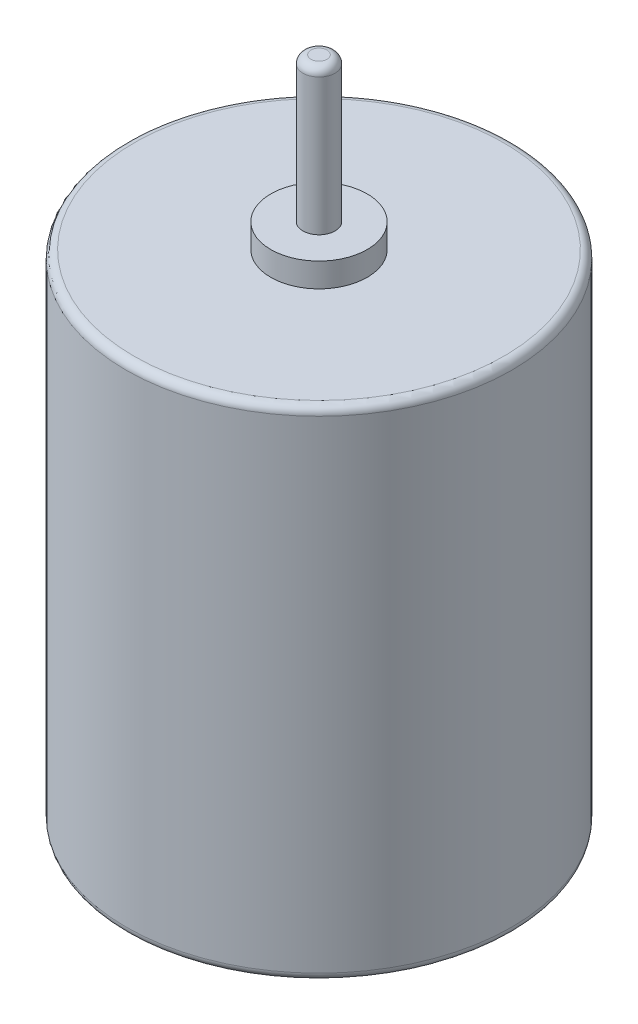
SolidWorks part; units mm, degrees
ref_plane "Front Plane" through (0, 0, 0) normal (0, 0, 1) x (1, 0, 0)
ref_plane "Top Plane" through (0, 0, 0) normal (0, 1, 0) x (1, 0, 0)
ref_plane "Right Plane" through (0, 0, 0) normal (1, 0, 0) x (0, 0, -1)
sketch "Sketch1" plane through (0, 0, 0) normal (0, 1, 0) x (1, 0, 0)
  circle A0 centre (0, 0) radius 12
  dimension "D1" = 24
extrude "Motor housing" add sketch "Sketch1" along normal blind 31
sketch "Sketch2" plane through (0, 31, 0) normal (0, 1, 0) x (1, 0, 0)
  circle A0 centre (0, 0) radius 3
  dimension "D1" = 6
extrude "Motor front nipple" add sketch "Sketch2" along normal blind 1.5
sketch "Sketch4" plane through (0, 32.5, 0) normal (0, 1, 0) x (1, 0, 0)
  circle A0 centre (0, 0) radius 1
  dimension "D1" = 2
extrude "Front axle" add sketch "Sketch4" along normal blind 9
fillet "Fillet1" radius 0.5 1 edges at (0, 41.5, 1)
fillet "Fillet2" radius 0.5 2 edges at (0, 0, 12) (0, 31, 12)
sketch "Sketch5" plane through (0, 0, 0) normal (0, -1, 0) x (1, 0, 0)
  circle A0 centre (0, 0) radius 4.5
  dimension "D1" = 9
extrude "Boss-Extrude1" add sketch "Sketch5" along normal blind 2
sketch "Sketch6" plane through (0, -2, 0) normal (0, -1, 0) x (1, 0, 0)
  circle A0 centre (0, 0) radius 1
  dimension "D1" = 2
extrude "Boss-Extrude2" add sketch "Sketch6" along normal blind 1
fillet "Fillet3" radius 0.5 2 edges at (0, -3, -1) (0, -2, -4.5)
